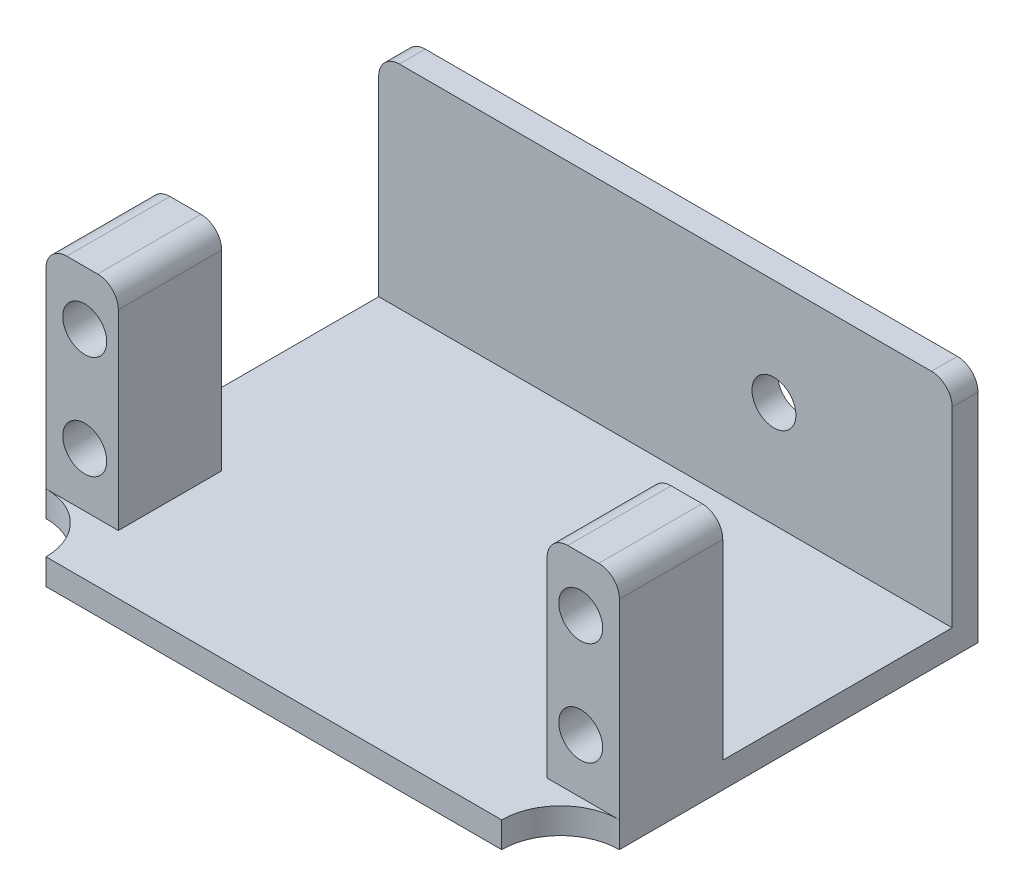
SolidWorks part; units mm, degrees
ref_plane "Front" through (0, 0, 0) normal (0, 0, 1) x (1, 0, 0)
ref_plane "Top" through (0, 0, 0) normal (0, 1, 0) x (1, 0, 0)
ref_plane "Right" through (0, 0, 0) normal (1, 0, 0) x (0, 0, -1)
sketch "Sketch1" plane through (0, 0, 0) normal (0, 1, 0) x (1, 0, 0)
  line L1 (0, 0) -> (55.5, 0)
  line L2 (0, 0) -> (0, 37.9)
  line L3 (0, 37.9) -> (55.5, 37.9)
  line L4 (55.5, 0) -> (55.5, 37.9)
  dimension "D1" = 37.9
  dimension "D2" = 55.5
extrude "bracketBase" add sketch "Sketch1" along normal blind 2.5
ref_plane "referencePlane1" through (0, 0, -8.2) normal (0, 0, 1) x (1, 0, 0)
sketch "Sketch2" plane through (0, 0, -8.2) normal (0, 0, 1) x (1, 0, 0)
  line L0 (27.75, 2.5) -> (27.75, 23) construction
  line L1 (0, 2.5) -> (7, 2.5)
  line L2 (0, 2.5) -> (0, 23)
  line L3 (0, 23) -> (7, 23)
  line L4 (7, 2.5) -> (7, 23)
  line L5 (0, 2.5) -> (55.5, 2.5) construction
  line L6 (55.5, 23) -> (48.5, 23)
  line L7 (48.5, 2.5) -> (48.5, 23)
  line L8 (55.5, 2.5) -> (48.5, 2.5)
  line L9 (55.5, 2.5) -> (55.5, 23)
  dimension "D1" = 20.5
  dimension "D2" = 7
extrude "servoMountingHoleTabs" add sketch "Sketch2" along normal blind 2.5
sketch "Sketch3" plane through (0, 0, -5.7) normal (0, 0, 1) x (1, 0, 0)
  line L0 (0, 12.75) -> (7, 12.75) construction
  line L3 (0, 23) -> (0, 2.5) construction
  line L4 (7, 2.5) -> (7, 23) construction
  line L5 (7, 23) -> (0, 23) construction
  line L6 (27.75, 2.5) -> (27.75, 23) construction
  line L7 (0, 2.5) -> (55.5, 2.5) construction
  circle A0 centre (3.75, 17.75) radius 2.125
  circle A1 centre (3.75, 7.75) radius 2.125
  circle A2 centre (51.75, 7.75) radius 2.125
  circle A3 centre (51.75, 17.75) radius 2.125
  dimension "D1" = 4.25
  dimension "D2" = 3.75
  dimension "D3" = 5.25
extrude "servoMountingHoles" cut sketch "Sketch3" against normal blind 2.5
sketch "Sketch4" plane through (0, 0, 0) normal (0, 1, 0) x (1, 0, 0)
  line L0 (55.5, 8.2) -> (55.5, 37.9) construction
  line L1 (0, 37.9) -> (55.5, 37.9)
  line L2 (0, 37.9) -> (0, 40.4)
  line L3 (0, 40.4) -> (55.5, 40.4)
  line L4 (55.5, 37.9) -> (55.5, 40.4)
  dimension "D1" = 2.5
extrude "baseWall" add sketch "Sketch4" along normal up to surface (23 mm away) up to face at (3.5, 23, -6.95)
sketch "Sketch6" plane through (0, 2.5, 0) normal (0, 1, 0) x (1, 0, 0)
  circle A0 centre (0, 0) radius 5.7
  circle A1 centre (55.5, 0) radius 5.7
extrude "baseTrim" cut sketch "Sketch6" against normal blind 2.5
fillet "Fillet1" radius 2 6 edges at (7, 23, -6.95) (48.5, 23, -6.95) (0, 23, -6.95) (55.5, 23, -6.95) (55.5, 23, -39.15) (0, 23, -39.15)
sketch "Sketch7" plane through (0, 0, -40.4) normal (0, 0, -1) x (-1, 0, 0)
  line L0 (0, 21) -> (0, 0) construction
  line L1 (-55.5, 0) -> (0, 0) construction
  circle A0 centre (-17.25, 12.75) radius 2.125
  dimension "D1" = 4.25
  dimension "D2" = 17.25
  dimension "D3" = 12.75
extrude "M4mountingHole" cut sketch "Sketch7" against normal blind 10
sketch "Sketch8" plane through (0, 0, -40.4) normal (0, 0, -1) x (-1, 0, 0)
  line L0 (-27.75, 23) -> (-27.75, 0) construction
  line L1 (-2, 23) -> (-53.5, 23) construction
  line L2 (-55.5, 0) -> (0, 0) construction
  circle A0 centre (-17.25, 12.75) radius 2.125 construction
  circle A1 centre (-17.25, 12.75) radius 2.125 construction
  circle A2 centre (-38.25, 12.75) radius 2.125
extrude "Cut-Extrude1" cut sketch "Sketch8" against normal blind 10
sketch "Sketch9" plane through (0, 0, -40.4) normal (0, 0, -1) x (-1, 0, 0)
  circle A0 centre (-17.25, 12.75) radius 2.125 construction
  circle A1 centre (-17.25, 12.75) radius 2.125
extrude "Boss-Extrude1" add sketch "Sketch9" against normal up to surface (2.5 mm away) up to face at (36.125, 12.75, -37.9)
sketch "Sketch10" plane through (0, 0, -8.2) normal (0, 0, -1) x (-1, 0, 0)
  line L4 (-48.5, 2.5) -> (-48.5, 21)
  line L5 (-50.5, 23) -> (-53.5, 23)
  line L6 (-55.5, 21) -> (-55.5, 2.5)
  line L7 (-55.5, 2.5) -> (-48.5, 2.5)
  line L8 (-48.5, 2.5) -> (-48.5, 21)
  line L9 (-50.5, 23) -> (-53.5, 23)
  line L10 (-55.5, 21) -> (-55.5, 2.5)
  line L11 (-55.5, 2.5) -> (-48.5, 2.5)
  line L12 (-2, 23) -> (-5, 23)
  line L13 (-7, 21) -> (-7, 2.5)
  line L14 (-7, 2.5) -> (0, 2.5)
  line L15 (0, 2.5) -> (0, 21)
  line L16 (-2, 23) -> (-5, 23)
  line L17 (-7, 21) -> (-7, 2.5)
  line L18 (-7, 2.5) -> (0, 2.5)
  line L19 (0, 2.5) -> (0, 21)
  circle A0 centre (-51.75, 17.75) radius 2.125 construction
  circle A1 centre (-51.75, 17.75) radius 2.125
  arc A2 (-48.5, 21) -> (-50.5, 23) centre (-50.5, 21) ccw
  arc A3 (-53.5, 23) -> (-55.5, 21) centre (-53.5, 21) ccw
  arc A4 (-48.5, 21) -> (-50.5, 23) centre (-50.5, 21) ccw
  arc A5 (-53.5, 23) -> (-55.5, 21) centre (-53.5, 21) ccw
  arc A6 (-5, 23) -> (-7, 21) centre (-5, 21) ccw
  arc A7 (0, 21) -> (-2, 23) centre (-2, 21) ccw
  arc A8 (-5, 23) -> (-7, 21) centre (-5, 21) ccw
  arc A9 (0, 21) -> (-2, 23) centre (-2, 21) ccw
  circle A10 centre (-51.75, 7.75) radius 2.125 construction
  circle A11 centre (-51.75, 7.75) radius 2.125
  circle A12 centre (-3.75, 17.75) radius 2.125 construction
  circle A13 centre (-3.75, 17.75) radius 2.125
  circle A14 centre (-3.75, 7.75) radius 2.125 construction
  circle A15 centre (-3.75, 7.75) radius 2.125
  dimension "D1" = 0
  dimension "D2" = 0
extrude "Boss-Extrude2" add sketch "Sketch10" along normal blind 7.5
